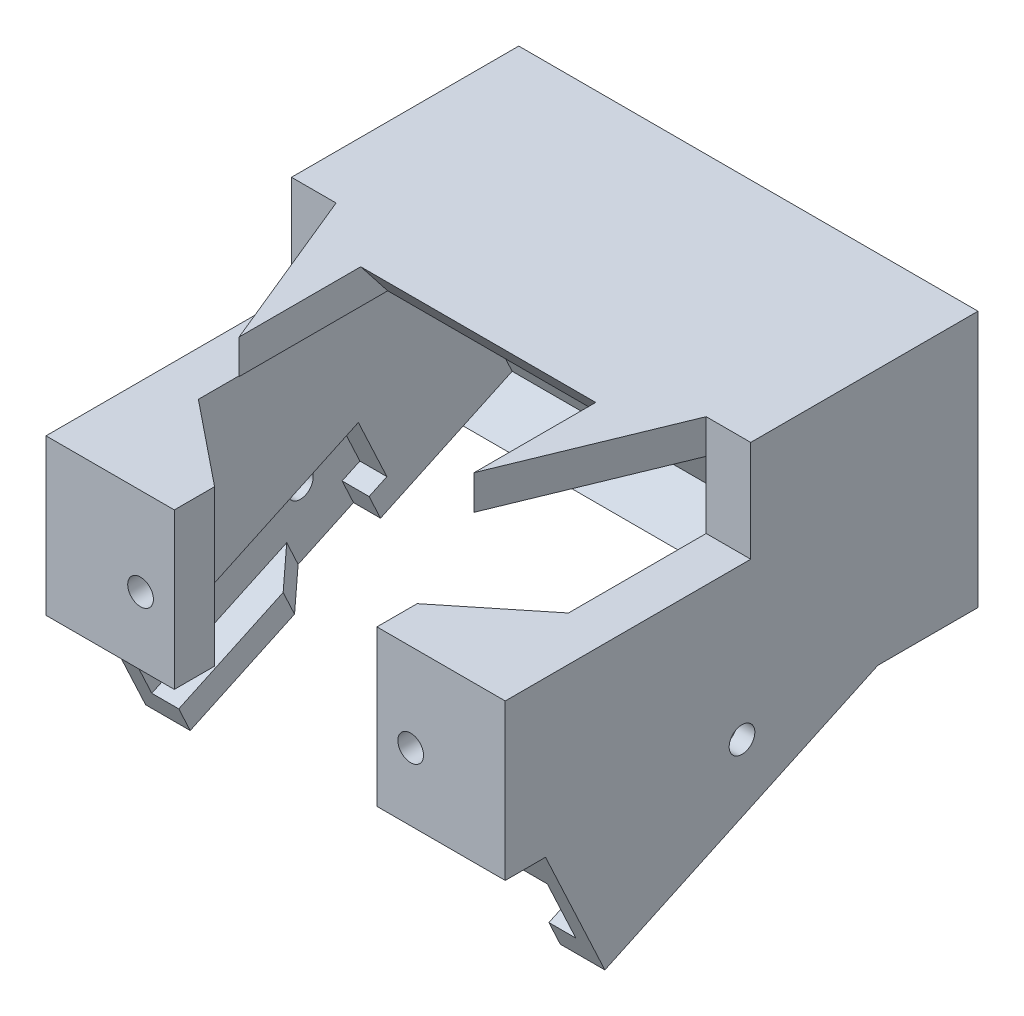
SolidWorks part; units mm, degrees
ref_plane "Alzado" through (0, 0, 0) normal (0, 0, 1) x (1, 0, 0)
ref_plane "Planta" through (0, 0, 0) normal (0, 1, 0) x (1, 0, 0)
ref_plane "Vista lateral" through (0, 0, 0) normal (1, 0, 0) x (0, 0, -1)
sketch "Croquis1" plane through (0, 0, 0) normal (0, 0, 1) x (1, 0, 0)
  line L1 (-57.6699, 25.4854) -> (-23.6699, 25.4854)
  line L2 (-57.6699, 25.4854) -> (-57.6699, 6.4854)
  line L3 (-57.6699, 6.4854) -> (-23.6699, 6.4854)
  line L4 (-23.6699, 25.4854) -> (-23.6699, 6.4854)
  dimension "D1" = 34
  dimension "D2" = 19
extrude "Saliente-Extruir1" add sketch "Croquis1" along normal blind 35
sketch "Croquis2" plane through (-23.6699, 0, 0) normal (1, 0, 0) x (0, 0, -1)
  line L0 (-27.6242, -2.939) -> (-7.4135, 6.4854)
  line L1 (-35, 6.4854) -> (0, 6.4854) construction
  line L7 (-27.6242, -2.939) -> (-32.0188, 6.4854)
  line L8 (-32.0188, 6.4854) -> (-7.4135, 6.4854)
extrude "Saliente-Extruir2" add sketch "Croquis2" against normal up to vertex (34 mm away)
sketch "Croquis5" plane through (0, 8.1666, 3.8082) normal (0, -0.9063, -0.4226) x (1, 0, 0)
  line L1 (-57.6699, 26.2781) -> (-23.6699, 26.2781) construction
  line L2 (-54.3699, 26.2781) -> (-26.9699, 26.2781)
  line L3 (-54.3699, 26.2781) -> (-54.3699, 3.9781)
  line L4 (-54.3699, 3.9781) -> (-26.9699, 3.9781)
  line L7 (-26.9699, 26.2781) -> (-26.9699, 3.9781)
  line L8 (-57.6699, 3.9781) -> (-23.6699, 3.9781) construction
  line L9 (-57.6699, 26.2781) -> (-57.6699, 3.9781) construction
  line L10 (-23.6699, 26.2781) -> (-23.6699, 3.9781) construction
  dimension "D1" = 3.3
  dimension "D2" = 3.3
extrude "Cortar-Extruir1" cut sketch "Croquis5" against normal blind 11
sketch "Croquis6" plane through (0, -1.6812, 3.6053) normal (0, -0.4226, 0.9063) x (1, 0, 0)
  line L1 (-54.3699, 20.0109) -> (-26.9699, 20.0109)
  line L2 (-54.3699, 20.0109) -> (-54.3699, 9.0109)
  line L3 (-54.3699, 9.0109) -> (-26.9699, 9.0109)
  line L4 (-26.9699, 20.0109) -> (-26.9699, 9.0109)
extrude "Cortar-Extruir2" cut sketch "Croquis6" against normal blind 4
sketch "Croquis7" plane through (0, 8.1666, 3.8082) normal (0, 0.9063, 0.4226) x (1, 0, 0)
  line L0 (-54.3699, 0.0219) -> (-26.9699, 0.0219) construction
  line L1 (-26.9699, -3.9781) -> (-36.9699, -3.9781)
  line L2 (-26.9699, -3.9781) -> (-26.9699, 0.0219)
  line L3 (-26.9699, 0.0219) -> (-36.9699, 0.0219)
  line L4 (-36.9699, -3.9781) -> (-36.9699, 0.0219)
  dimension "D1" = 10
extrude "Cortar-Extruir3" cut sketch "Croquis7" against normal blind 4
sketch "Croquis8" plane through (0, -11.1056, 23.816) normal (0, -0.4226, 0.9063) x (1, 0, 0)
  line L0 (-26.9699, 9.0109) -> (-26.9699, 19.4095) construction
  line L1 (-26.9699, 11.0109) -> (-24.9699, 11.0109)
  line L2 (-26.9699, 11.0109) -> (-26.9699, 16.0109)
  line L3 (-26.9699, 16.0109) -> (-24.9699, 16.0109)
  line L4 (-24.9699, 11.0109) -> (-24.9699, 16.0109)
  line L5 (-26.9699, 9.0109) -> (-23.6699, 9.0109) construction
  line L6 (-54.3699, 19.4095) -> (-54.3699, 9.0109) construction
  line L7 (-54.3699, 11.0109) -> (-56.3699, 11.0109)
  line L8 (-54.3699, 11.0109) -> (-54.3699, 16.0109)
  line L9 (-54.3699, 16.0109) -> (-56.3699, 16.0109)
  line L10 (-56.3699, 11.0109) -> (-56.3699, 16.0109)
  line L11 (-57.6699, 9.0109) -> (-54.3699, 9.0109) construction
  dimension "D1" = 2
  dimension "D2" = 5
  dimension "D3" = 2
  dimension "D4" = 2
  dimension "D5" = 2
  dimension "D6" = 5
extrude "Cortar-Extruir4" cut sketch "Croquis8" against normal blind 17
sketch "Croquis14" plane through (-54.3699, 0, 0) normal (1, 0, 0) x (0, 0, -1)
  line L2 (-32.8434, 18.9016) -> (-17.1643, 26.2129)
  line L3 (-32.273, 7.0304) -> (-32.4208, 17.9953)
  line L5 (-32.4208, 17.9953) -> (-32.8434, 18.9016)
  line L6 (-8.4371, 18.1453) -> (-16.7416, 25.3066)
  line L8 (-16.7416, 25.3066) -> (-17.1643, 26.2129)
  line L9 (-32.273, 7.0304) -> (-8.4371, 18.1453)
extrude "Cortar-Extruir7" cut sketch "Croquis14" along normal up to vertex
sketch "Croquis15" plane through (0, 0, 35) normal (0, 0, 1) x (1, 0, 0)
  line L0 (-40.6699, 6.4854) -> (-48.1699, 6.4854)
  line L1 (-57.6699, 6.4854) -> (-23.6699, 6.4854) construction
  line L2 (-48.1699, 6.4854) -> (-48.1699, 25.4854)
  line L3 (-23.6699, 25.4854) -> (-57.6699, 25.4854) construction
  line L4 (-48.1699, 25.4854) -> (-33.1699, 25.4854)
  line L5 (-33.1699, 25.4854) -> (-33.1699, 6.4854)
  line L6 (-33.1699, 6.4854) -> (-40.6699, 6.4854)
extrude "Cortar-Extruir8" cut sketch "Croquis15" against normal blind 21
sketch "Croquis17" plane through (0, 25.4854, 0) normal (0, 1, 0) x (1, 0, 0)
  line L0 (-57.6699, -35) -> (-57.6699, 0) construction
  line L1 (-23.6699, -35) -> (-57.6699, -35)
  line L2 (-23.6699, -35) -> (-23.6699, -16.825)
  line L3 (-23.6699, -16.825) -> (-57.6699, -16.825)
  line L4 (-57.6699, -35) -> (-57.6699, -16.825)
extrude "Cortar-Extruir10" cut sketch "Croquis17" against normal up to vertex (7.4901 mm away) up to point (-33.1699, 17.9953, 32.4208)
sketch "Croquis19" plane through (-48.1699, 0, 0) normal (1, 0, 0) x (0, 0, -1)
  line L0 (-32.0188, 6.4854) -> (-32.0188, 17.9953)
  line L1 (-32.0188, 17.9953) -> (-32.4208, 17.9953)
  line L2 (-32.4208, 17.9953) -> (-32.273, 7.0304)
  line L3 (-32.273, 7.0304) -> (-32.0188, 6.4854)
extrude "Saliente-Extruir3" add sketch "Croquis19" against normal up to vertex (9.5 mm away)
sketch "Croquis20" plane through (0, 6.4854, 0) normal (0, -1, 0) x (1, 0, 0)
  line L0 (-48.1699, 32.0188) -> (-54.3699, 27.0188)
  line L1 (-54.3699, 27.0188) -> (-54.3699, 32.0188)
  line L2 (-54.3699, 32.0188) -> (-48.1699, 32.0188)
extrude "Saliente-Extruir4" add sketch "Croquis20" against normal up to vertex
sketch "Croquis21" plane through (-33.1699, 0, 0) normal (-1, 0, 0) x (0, 0, 1)
  line L0 (32.0188, 6.4854) -> (32.0188, 17.9953)
  line L1 (32.0188, 17.9953) -> (32.4208, 17.9953)
  line L2 (32.4208, 17.9953) -> (32.273, 7.0304)
  line L3 (32.273, 7.0304) -> (32.0188, 6.4854)
extrude "Saliente-Extruir5" add sketch "Croquis21" against normal up to vertex
sketch "Croquis22" plane through (0, 6.4854, 0) normal (0, -1, 0) x (1, 0, 0)
  line L0 (-26.9699, 32.0188) -> (-26.9699, 27.0188)
  line L1 (-26.9699, 27.0188) -> (-33.1699, 32.0188)
  line L2 (-33.1699, 32.0188) -> (-26.9699, 32.0188)
extrude "Saliente-Extruir6" add sketch "Croquis22" against normal up to vertex
sketch "Croquis23" plane through (0, 0, 0) normal (0, 0, -1) x (-1, 0, 0)
  line L0 (23.6699, 25.4854) -> (57.6699, 25.4854) construction
  line L2 (23.6699, 6.4854) -> (23.6699, 25.4854) construction
  line L3 (57.6699, 25.4854) -> (57.6699, 6.4854) construction
  circle A0 centre (30.6699, 19.4854) radius 0.95
  circle A1 centre (50.6699, 19.4854) radius 0.95
  circle A2 centre (30.6699, 11.4854) radius 0.95
  circle A3 centre (50.6699, 11.4854) radius 0.95
  dimension "D1" = 6
  dimension "D3" = 6
  dimension "D5" = 8
  dimension "D2" = 7
  dimension "D4" = 7
  dimension "D6" = 8
extrude "Cortar-Extruir11" cut sketch "Croquis23" against normal blind 6
sketch "Croquis24" plane through (0, 0, 35) normal (0, 0, 1) x (1, 0, 0)
  circle A0 centre (-50.6699, 11.4854) radius 0.95
  circle A1 centre (-30.6699, 11.4854) radius 0.95
extrude "Cortar-Extruir12" cut sketch "Croquis24" against normal blind 2.5
sketch "Croquis28" plane through (-23.6699, 0, 0) normal (1, 0, 0) x (0, 0, -1)
  line L0 (-27.6242, -2.939) -> (-7.4135, 6.4854) construction
  line L1 (-32.0188, 6.4854) -> (-27.6242, -2.939) construction
  circle A0 centre (-17.4721, 6.7603) radius 0.95
  dimension "D1" = 4.5
  dimension "D2" = 13.3
extrude "Cortar-Extruir13" cut sketch "Croquis28" against normal up to vertex
sketch "Croquis29" plane through (0, 0, 14) normal (0, 0, 1) x (1, 0, 0)
  line L0 (-40.6699, 25.4854) -> (-54.3699, 25.4854)
  line L1 (-33.1699, 25.4854) -> (-48.1699, 25.4854) construction
  line L2 (-54.3699, 25.4854) -> (-54.3699, 22.9424)
  line L3 (-54.3699, 22.9424) -> (-26.9699, 22.9424)
  line L4 (-26.9699, 22.9424) -> (-26.9699, 25.4854)
  line L5 (-26.9699, 25.4854) -> (-40.6699, 25.4854)
extrude "Cortar-Extruir14" cut sketch "Croquis29" along normal up to vertex
sketch "Croquis30" plane through (0, 25.4854, 0) normal (0, 1, 0) x (1, 0, 0)
  line L0 (-54.3699, -14) -> (-49.3699, -14)
  line L1 (-26.9699, -14) -> (-54.3699, -14) construction
  line L2 (-49.3699, -29) -> (-49.3699, -20)
  line L3 (-54.3699, -14) -> (-54.3699, -16.825)
  line L4 (-54.3699, -16.825) -> (-49.3699, -29)
  line L5 (-26.9699, -14) -> (-31.9699, -14)
  line L6 (-26.9699, -14) -> (-26.9699, -16.825)
  line L7 (-26.9699, -16.825) -> (-31.9699, -29)
  line L8 (-31.9699, -29) -> (-31.9699, -20)
  line L9 (-31.9699, -20) -> (-49.3699, -20)
  line L10 (-49.3699, -14) -> (-31.9699, -14)
extrude "Saliente-Extruir7" add sketch "Croquis30" against normal up to vertex
sketch "Croquis31" plane through (-49.3699, 0, 0) normal (1, 0, 0) x (0, 0, -1)
  line L0 (-20, 25.4854) -> (-20, 22.9424)
  line L1 (-20, 22.9424) -> (-18, 22.9424)
  line L2 (-18, 22.9424) -> (-20, 25.4854)
extrude "Cortar-Extruir15" cut sketch "Croquis31" along normal up to vertex
sketch "Croquis33" plane through (-56.3699, 0, 0) normal (1, 0, 0) x (0, 0, -1)
  line L0 (-19.5168, 5.8213) -> (-17.4721, 1.3688)
  line L1 (-17.4721, 1.3688) -> (-13.3607, 3.2568)
  line L2 (-13.3607, 3.2568) -> (-15.4274, 7.6992)
  arc A0 (-19.5168, 5.8213) -> (-15.4274, 7.6992) centre (-17.4721, 6.7603) cw
extrude "Cortar-Extruir16" cut sketch "Croquis33" along normal up to vertex
sketch "Croquis34" plane through (0, 8.1666, 3.8082) normal (0, -0.9063, -0.4226) x (1, 0, 0)
  line L0 (-26.9699, 17.7544) -> (-26.9699, 14.8034)
  line L1 (-54.3699, 17.7544) -> (-54.3699, 14.8034)
  line L2 (-54.3699, 26.2781) -> (-54.3699, 15.2544) construction
  line L3 (-54.3699, 17.7544) -> (-56.3699, 15.2544)
  line L6 (-24.9699, 15.2544) -> (-26.9699, 17.7544)
  line L7 (-54.3699, 14.8034) -> (-56.3699, 14.8034)
  line L8 (-56.3699, 15.2544) -> (-56.3699, 10.7321) construction
  line L9 (-56.3699, 14.8034) -> (-56.3699, 15.2544)
  line L10 (-26.9699, 14.8034) -> (-24.9699, 14.8034)
  line L11 (-24.9699, 14.8034) -> (-24.9699, 15.2544)
extrude "Cortar-Extruir17" cut sketch "Croquis34" against normal up to vertex
